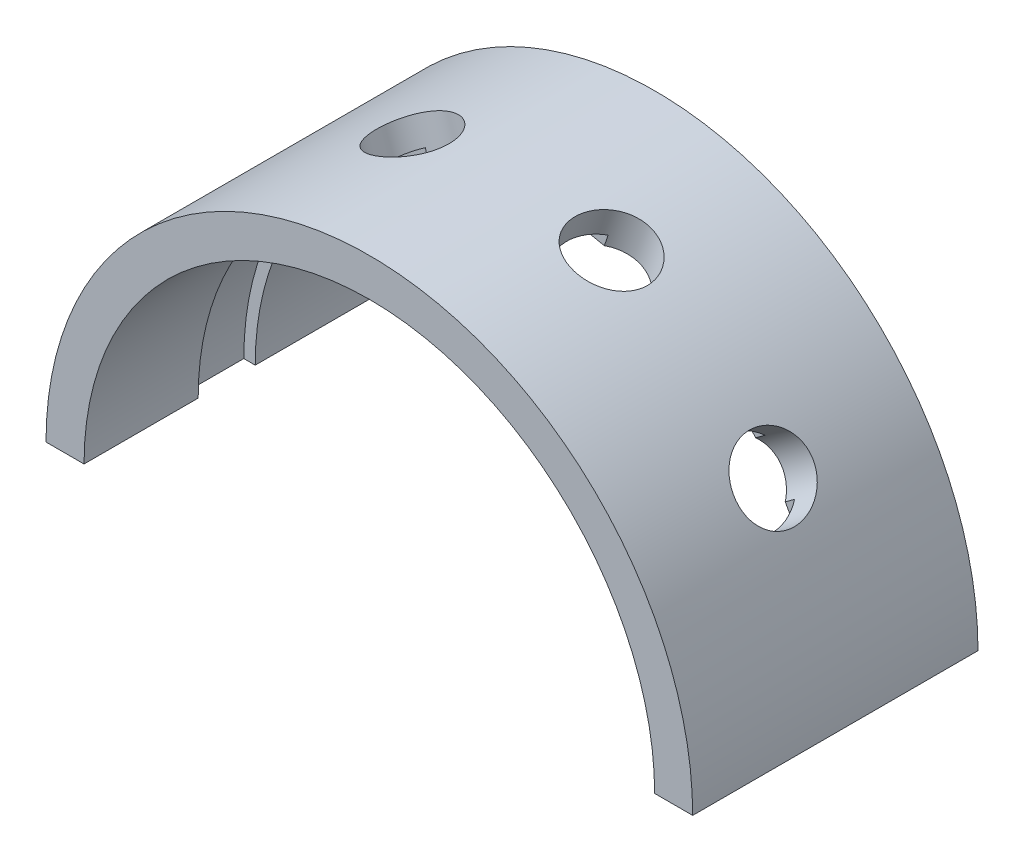
SolidWorks part; units mm, degrees
material "Plain Carbon Steel"
ref_plane "Front Plane" through (0, 0, 0) normal (0, 0, 1) x (1, 0, 0)
ref_plane "Top Plane" through (0, 0, 0) normal (0, 1, 0) x (1, 0, 0)
ref_plane "Right Plane" through (0, 0, 0) normal (1, 0, 0) x (0, 0, -1)
sketch "Sketch1" plane through (0, 0, 0) normal (0, 0, 1) x (1, 0, 0)
  arc A0 (-8.5, 0) -> (8.5, 0) centre (0, 0) cw
  dimension "D1" = 8.5
sketch "Sketch2" plane through (0, 0, 0) normal (0, 1, 0) x (1, 0, 0)
  line L0 (-7.5, -3.75) -> (-7.5, -0.75)
  line L1 (-7.5, -0.75) -> (-7.8, -0.75)
  line L2 (-7.8, -0.75) -> (-7.8, 0.75)
  line L3 (-7.8, 0.75) -> (-7.5, 0.75)
  line L4 (-7.5, 0.75) -> (-7.5, 3.75)
  line L5 (-7.5, 3.75) -> (-8.5, 3.75)
  line L6 (-8.5, 3.75) -> (-8.5, -3.75)
  line L7 (-8.5, -3.75) -> (-7.5, -3.75)
  point P3 (-8.5, 0)
  dimension "D1" = 7.5
  dimension "D2" = 7.5
  dimension "D3" = 0.7
  dimension "D4" = 1.5
sweep "Sweep1" add profiles "Sketch2" path "Sketch1"
sketch "Sketch3" plane through (0, 0, 0) normal (0, 0, 1) x (1, 0, 0)
  line L0 (0, 0) -> (0, 19.4491) construction
  line L1 (0, 0) -> (6.3285, 19.477) construction
  line L2 (0, 0) -> (-6.4321, 19.796) construction
  line L3 (0, 0) -> (-18.2798, 13.281) construction
  line L4 (0, 0) -> (17.3766, 12.6249) construction
  line L5 (4.9385, 3.588) -> (15.3759, 11.1712)
  line L6 (15.3759, 11.1712) -> (15.9637, 10.3622)
  line L7 (15.9637, 10.3622) -> (5.5263, 2.779)
  line L8 (5.5263, 2.779) -> (4.9385, 3.588)
  point P11 (6.3285, 1.5655)
  dimension "D1" = 18
  dimension "D2" = 36
  dimension "D3" = 36
  dimension "D4" = 36
  dimension "D5" = 1
revolve "Cut-Revolve1" cut sketch "Sketch3" angle 360 about L5
ref_axis "Axis1" through (0, 0, -11.55) along (0, 0, 1)
pattern_circular "CirPattern1" count 4 over 108 about axis through (0, 0, -11.55) along (0, 0, 1) of "Cut-Revolve1"
